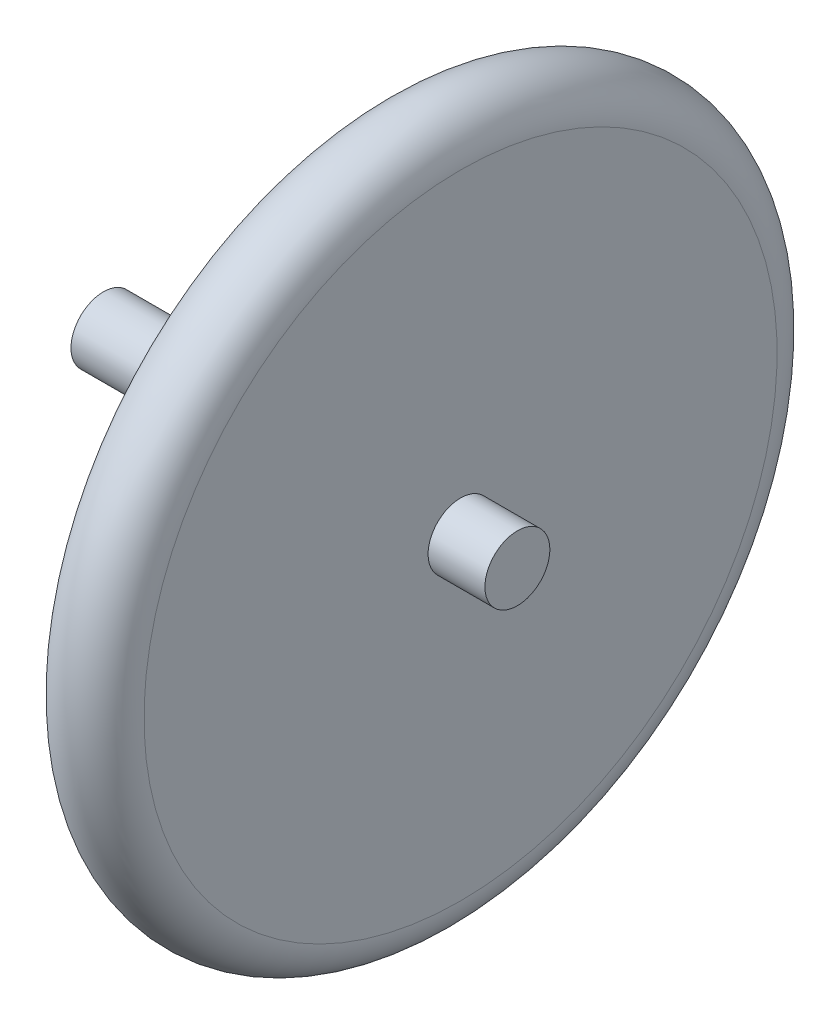
SolidWorks part; units mm, degrees
ref_plane "Front" through (0, 0, 0) normal (0, 0, 1) x (1, 0, 0)
ref_plane "Top" through (0, 0, 0) normal (0, 1, 0) x (1, 0, 0)
ref_plane "Right" through (0, 0, 0) normal (1, 0, 0) x (0, 0, -1)
sketch "Esquisse1" plane through (0, 0, 0) normal (0, 0, 1) x (1, 0, 0)
  line L1 (0, 0) -> (-2.5, 0) construction
  line L2 (0, 0) -> (0, 22) construction
  line L3 (0, 22) -> (-2.5, 22) construction
  line L4 (-2.5, 0) -> (-2.5, 22) construction
  line L13 (-2.5, 19.5) -> (-2.5, 2)
  line L15 (2.5, 19.5) -> (2.5, 2)
  line L16 (0, 0) -> (-19.5, 0)
  line L17 (-19.5, 0) -> (-19.5, 2)
  line L18 (-19.5, 2) -> (-2.5, 2)
  line L19 (0, 0) -> (6, 0)
  line L20 (6, 0) -> (6, 2)
  line L21 (6, 2) -> (2.5, 2)
  arc A1 (-2.5, 19.5) -> (2.5, 19.5) centre (0, 19.5) cw
  dimension "D1" = 5
  dimension "D2" = 22
  dimension "D3" = 25.5
  dimension "D4" = 3.5
  dimension "D5" = 2
revolve "Révolution1" add sketch "Esquisse1" angle 360 about L1
